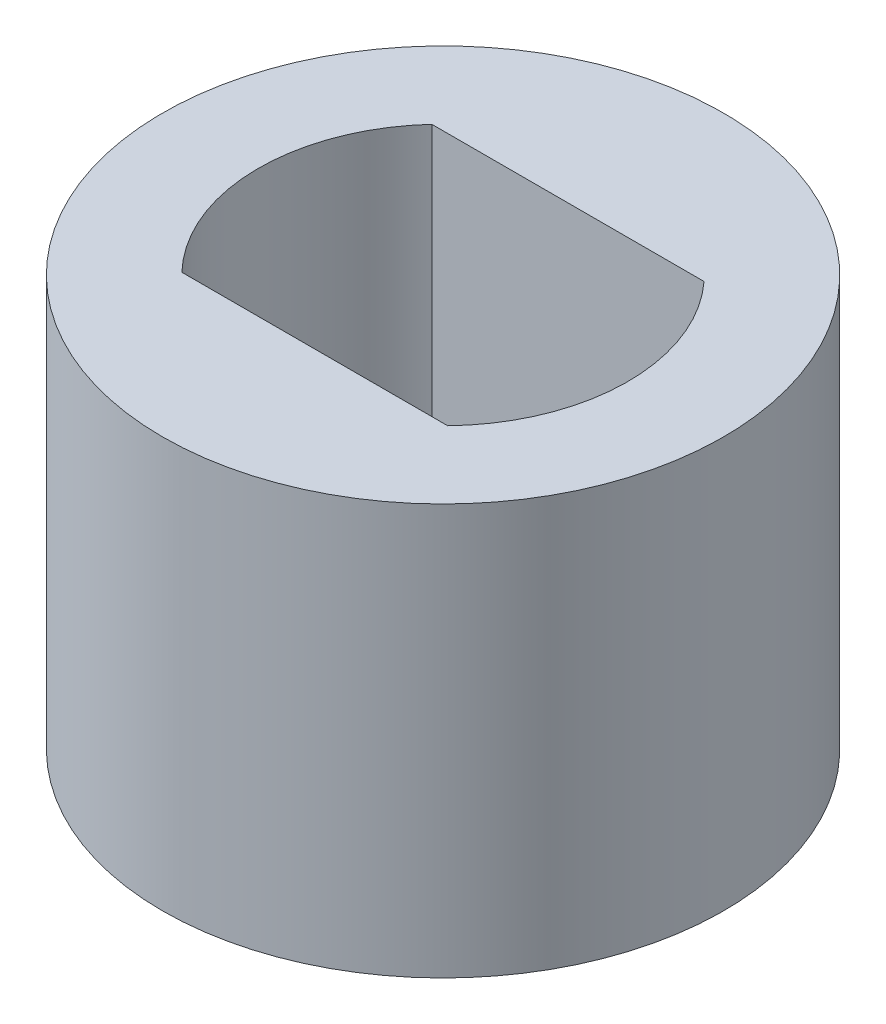
SolidWorks part; units mm, degrees
ref_plane "Front Plane" through (0, 0, 0) normal (0, 0, 1) x (1, 0, 0)
ref_plane "Top Plane" through (0, 0, 0) normal (0, 1, 0) x (1, 0, 0)
ref_plane "Right Plane" through (0, 0, 0) normal (1, 0, 0) x (0, 0, -1)
sketch "Sketch1" plane through (0, 0, 0) normal (0, 1, 0) x (1, 0, 0)
  circle A0 centre (0, 0) radius 4.1
  dimension "D1" = 8.2
extrude "Boss-Extrude1" add sketch "Sketch1" along normal blind 6
sketch "Sketch2" plane through (0, 6, 0) normal (0, 1, 0) x (1, 0, 0)
  line L0 (1.9898, 1.825) -> (-1.9898, 1.825)
  line L1 (-1.9428, -1.875) -> (1.9428, -1.875)
  arc A0 (-1.9898, 1.825) -> (-1.9428, -1.875) centre (0, 0) ccw
  arc A1 (1.9428, -1.875) -> (1.9898, 1.825) centre (0, 0) ccw
  point P5 (0, 0)
  point P7 (0.0332, -0.105)
  dimension "D1" = 5.4
  dimension "D2" = 3.7
  dimension "D3" = 1.825
  dimension "D4" = 1.875
extrude "Cut-Extrude1" cut sketch "Sketch2" against normal blind 8
